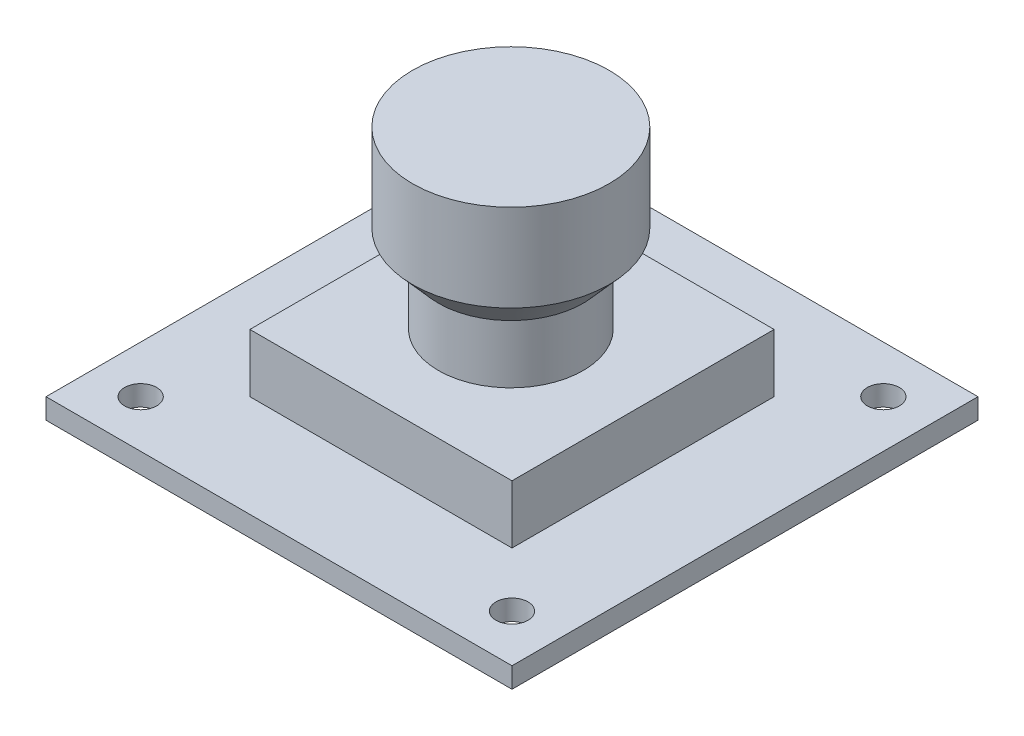
SolidWorks part; units mm, degrees
ref_plane "前视基准面" through (0, 0, 0) normal (0, 0, 1) x (1, 0, 0)
ref_plane "上视基准面" through (0, 0, 0) normal (0, 1, 0) x (1, 0, 0)
ref_plane "右视基准面" through (0, 0, 0) normal (1, 0, 0) x (0, 0, -1)
sketch "草图1" plane through (0, 0, 0) normal (0, 1, 0) x (1, 0, 0)
  line L0 (16, 32) -> (16, -15.8922) construction
  line L1 (0, 0) -> (32, 0)
  line L2 (0, 0) -> (0, 32)
  line L3 (0, 32) -> (32, 32)
  line L4 (32, 0) -> (32, 32)
  line L5 (0, 16) -> (48.5423, 16) construction
  circle A0 centre (3.25, 28.75) radius 1.1
  circle A1 centre (28.75, 28.75) radius 1.1
  circle A2 centre (28.75, 3.25) radius 1.1
  circle A3 centre (3.25, 3.25) radius 1.1
  dimension "D3" = 2.2
  dimension "D4" = 25.5
  dimension "D5" = 25.5
  dimension "D6" = 3.25
  dimension "D1" = 32
  dimension "D2" = 32
extrude "凸台-拉伸1" add sketch "草图1" along normal blind 1.4
sketch "草图2" plane through (0, 1.4, 0) normal (0, 1, 0) x (1, 0, 0)
  line L0 (16, 32) -> (16, -0.6336) construction
  line L1 (32, 32) -> (0, 32) construction
  line L2 (0, 16) -> (34.8046, 16) construction
  line L3 (0, 32) -> (0, 0) construction
  line L5 (7, 7) -> (25, 7)
  line L6 (7, 7) -> (7, 25)
  line L7 (7, 25) -> (25, 25)
  line L8 (25, 7) -> (25, 25)
  line L9 (7, 7) -> (25, 25) construction
  line L10 (7, 25) -> (25, 7) construction
  point P8 (16, 16)
  dimension "D1" = 18
  dimension "D2" = 18
extrude "凸台-拉伸2" add sketch "草图2" along normal blind 4
sketch "草图3" plane through (0, 5.4, 0) normal (0, 1, 0) x (1, 0, 0)
  line L0 (16, 25) -> (16, 10.2056) construction
  line L1 (25, 25) -> (7, 25) construction
  line L2 (7, 16) -> (24.84, 16) construction
  line L3 (7, 25) -> (7, 7) construction
  circle A0 centre (15.92, 16) radius 6.75
  dimension "D1" = 13.5
extrude "凸台-拉伸3" add sketch "草图3" along normal blind 12
ref_plane "基准面1" through (0, 0, -16) normal (0, 0, 1) x (1, 0, 0)
sketch "草图4" plane through (0, 0, -16) normal (0, 0, 1) x (1, 0, 0)
  line L0 (9.17, 11.4) -> (10.9475, 9.4)
  line L1 (9.17, 17.4) -> (9.17, 5.4) construction
  line L2 (10.9475, 9.4) -> (10.9475, 5.4)
  line L3 (7, 5.4) -> (25, 5.4) construction
  line L4 (10.9475, 5.4) -> (9.17, 5.4)
  line L5 (9.17, 5.4) -> (9.17, 11.4)
  dimension "D1" = 4
  dimension "D2" = 6
ref_axis "基准轴1" through (15.92, 17.4, -16) along (0, -1, 0)
revolve "切除-旋转1" cut sketch "草图4" angle 360 about axis through (15.92, 17.4, -16) along (0, -1, 0)
sketch "草图5" plane through (0, 0, 0) normal (0, -1, 0) x (1, 0, 0)
  line L1 (0.2499, -27.65) -> (4.2499, -27.65)
  line L2 (0.2499, -27.65) -> (0.2499, -18.65)
  line L3 (0.2499, -18.65) -> (4.2499, -18.65)
  line L4 (4.2499, -27.65) -> (4.2499, -18.65)
  circle A0 centre (3.25, -28.75) radius 1.1 construction
  dimension "D1" = 4
  dimension "D2" = 9
extrude "凸台-拉伸4" add sketch "草图5" along normal blind 8
sketch "草图6" plane through (0, -8, 0) normal (0, -1, 0) x (1, 0, 0)
  circle A0 centre (1.9505, -20.5137) radius 0.531
  circle A3 centre (1.9505, -22.5137) radius 0.531
  circle A4 centre (1.9505, -24.5137) radius 0.531
  circle A5 centre (1.9505, -26.5137) radius 0.531
  dimension "D1" = 4
extrude "凸台-拉伸5" add sketch "草图6" along normal blind 4
